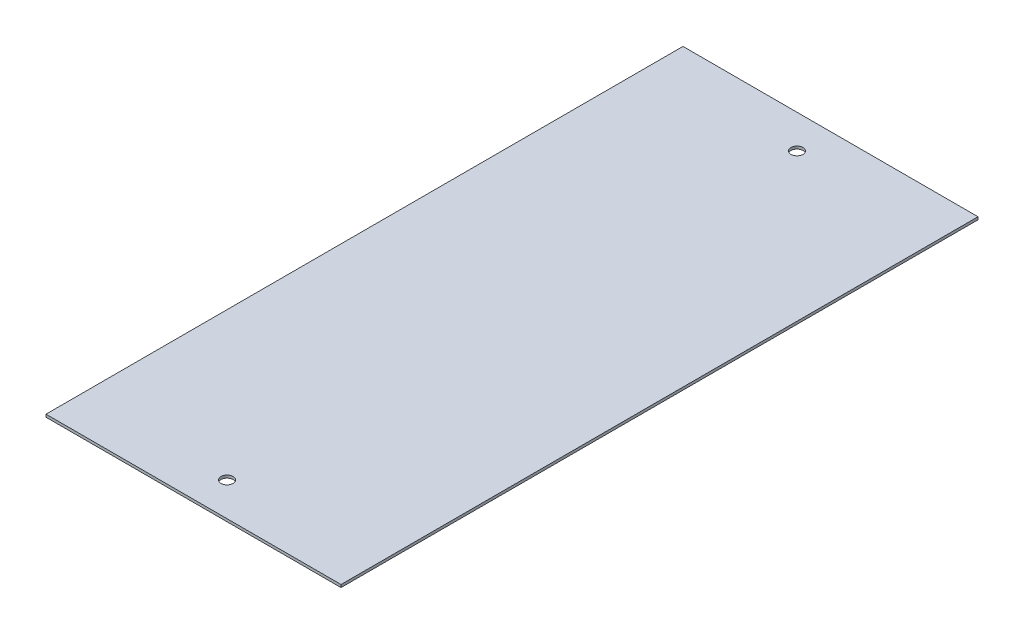
SolidWorks part; units mm, degrees
material "Chapa F.F 1020 - 2 mm"
ref_plane "Plano frontal" through (0, 0, 0) normal (0, 0, 1) x (1, 0, 0)
ref_plane "Plano superior" through (0, 0, 0) normal (0, 1, 0) x (1, 0, 0)
ref_plane "Plano direito" through (0, 0, 0) normal (1, 0, 0) x (0, 0, -1)
sketch "Esboço1" plane through (0, 0, 0) normal (0, 0, 1) x (1, 0, 0)
  line L1 (0, 0) -> (220, 0)
  line L2 (0, 0) -> (0, 2)
  line L3 (0, 2) -> (220, 2)
  line L4 (220, 0) -> (220, 2)
  dimension "D1" = 220
  dimension "D2" = 2
extrude "Ressalto-extrusão1" add sketch "Esboço1" along normal blind 475
sketch "Esboço3" plane through (0, 2, 0) normal (0, 1, 0) x (1, 0, 0)
  line L0 (110, 0) -> (110, -475) construction
  line L1 (220, 0) -> (0, 0) construction
  line L2 (220, -475) -> (0, -475) construction
  line L3 (0, -237.5) -> (220, -237.5) construction
  line L4 (0, -475) -> (0, 0) construction
  line L5 (220, -475) -> (220, 0) construction
  point P6 (110, -25)
  point P7 (110, -450)
  dimension "D1" = 25
hole_wizard "Furo com folga de M81" positions "3DSketch1" profile "Esboço4" hole size "M8" standard "ISO"
sketch3d "3DSketch1"
  point P0 (110, 2, 25)
  point P3 (110, 2, 450)
sketch "Esboço4" plane through (110, 2, 25) normal (1, 0, 0) x (0, 0, 1)
  line L0 (0, 0) -> (0, 12.7039)
  line L1 (0, 12.7039) -> (4.5, 10)
  line L2 (4.5, 10) -> (4.5, 0)
  line L5 (4.5, 0) -> (0, 0)
  line L10 (0, 12.7039) -> (-4.5, 10) construction
  line L11 (0, -6.35) -> (0, 107.95) construction
  dimension "Hole Dia." = 9
  dimension "Hole Depth" = 10
  dimension "Drill Angle" = 118
